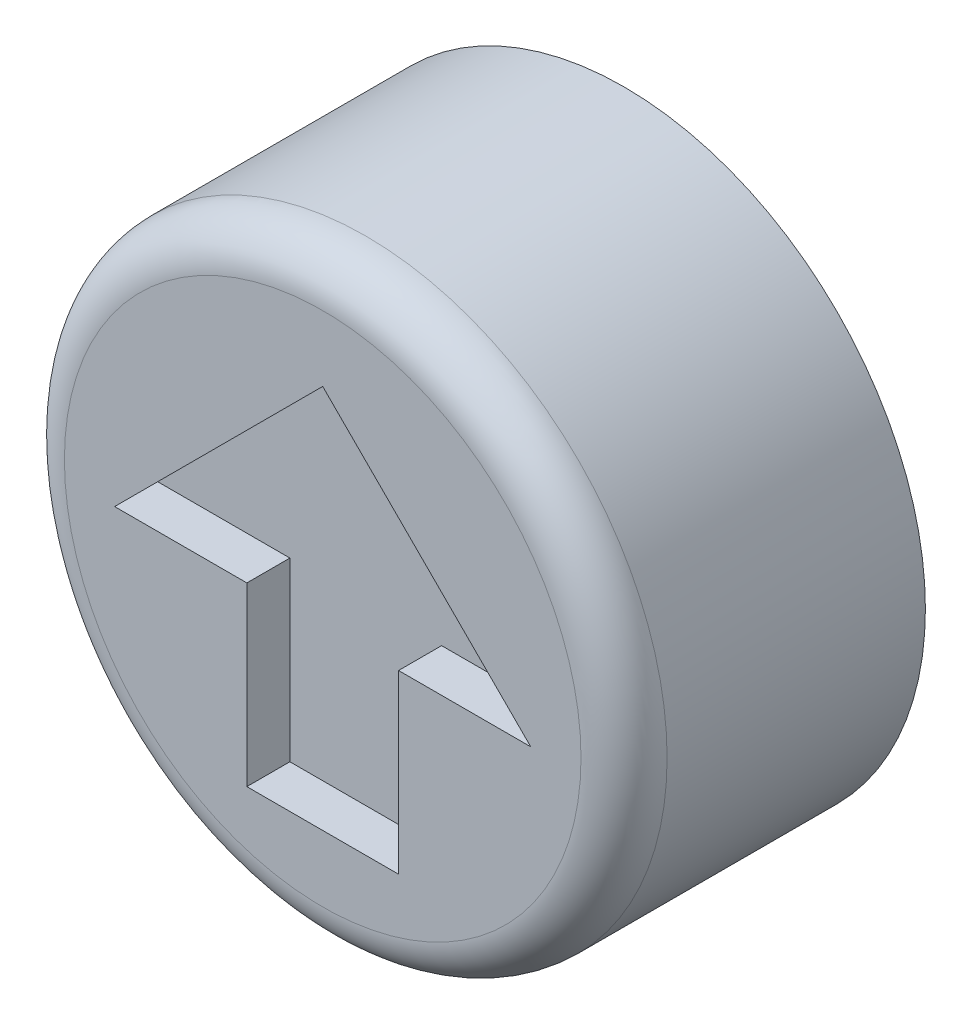
SolidWorks part; units mm, degrees
ref_plane "前视基准面" through (0, 0, 0) normal (0, 0, 1) x (1, 0, 0)
ref_plane "上视基准面" through (0, 0, 0) normal (0, 1, 0) x (1, 0, 0)
ref_plane "右视基准面" through (0, 0, 0) normal (1, 0, 0) x (0, 0, -1)
sketch "草图1" plane through (0, 0, 0) normal (0, 0, 1) x (1, 0, 0)
  circle A0 centre (0, 0) radius 1.6
  circle A1 centre (0, 0) radius 7
  dimension "D1" = 3.2
  dimension "D2" = 14
extrude "凸台-拉伸1" add sketch "草图1" along normal blind 5
sketch "草图2" plane through (0, 0, 5) normal (0, 0, 1) x (1, 0, 0)
  circle A0 centre (0, 0) radius 7
  dimension "D1" = 14
extrude "凸台-拉伸2" add sketch "草图2" along normal blind 2
fillet "圆角1" radius 1 1 edges at (7, 0, 7)
sketch "草图4" plane through (0, 0, 7) normal (0, 0, 1) x (1, 0, 0)
  line L0 (0, 0) -> (0, 50000) construction
  line L1 (0, 4.4729) -> (-4.8332, -0.3603)
  line L2 (-4.8332, -0.3603) -> (-1.7621, -0.3603)
  line L3 (-1.7621, -0.3603) -> (-1.7621, -4.4586)
  line L4 (-1.7621, -4.4586) -> (1.7621, -4.4586)
  line L5 (1.7621, -0.3603) -> (1.7621, -4.4586)
  line L6 (4.8332, -0.3603) -> (1.7621, -0.3603)
  line L7 (0, 4.4729) -> (4.8332, -0.3603)
  point P10 (0, -4.4586)
extrude "切除-拉伸1" cut sketch "草图4" against normal blind 1
